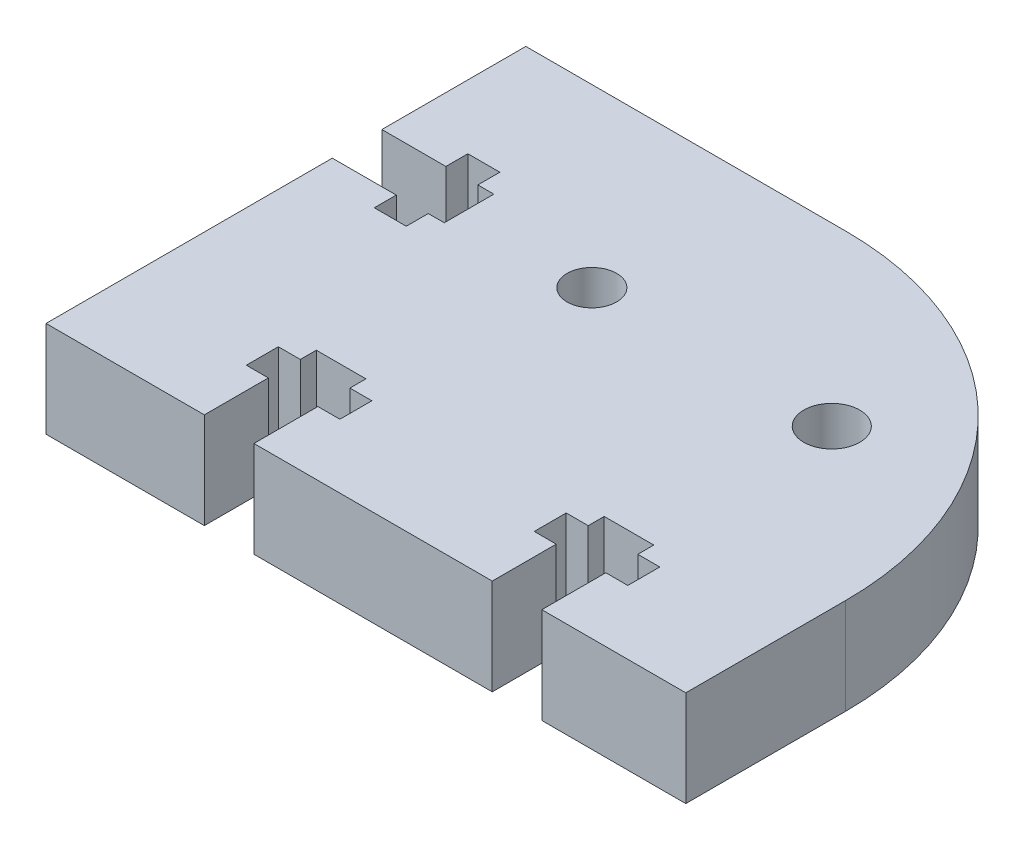
SolidWorks part; units mm, degrees
ref_plane "Płaszczyzna przednia" through (0, 0, 0) normal (0, 0, 1) x (1, 0, 0)
ref_plane "Płaszczyzna górna" through (0, 0, 0) normal (0, 1, 0) x (1, 0, 0)
ref_plane "Płaszczyzna prawa" through (0, 0, 0) normal (1, 0, 0) x (0, 0, -1)
sketch "Szkic3" plane through (0, 0, 0) normal (0, 1, 0) x (1, 0, 0)
  line L0 (-425.4385, -113.1796) -> (-425.4385, -103.1796)
  line L1 (-425.4385, -113.1796) -> (-465.4385, -113.1796)
  line L2 (-445.4385, -83.1796) -> (-465.4385, -83.1796)
  line L3 (-465.4385, -113.1796) -> (-465.4385, -83.1796)
  arc A0 (-425.4385, -103.1796) -> (-445.4385, -83.1796) centre (-445.4385, -103.1796) ccw
  dimension "D3" = 20
  dimension "D1" = 40
  dimension "D2" = 30
extrude "Dodanie-wyciągnięcie1" add sketch "Szkic3" along normal blind 6
sketch "Szkic4" plane through (0, 6, 0) normal (0, 1, 0) x (1, 0, 0)
  line L0 (-434.4385, -113.1796) -> (-437.5385, -113.1796)
  line L1 (-434.4385, -113.1796) -> (-434.4385, -109.1796)
  line L2 (-437.5385, -113.1796) -> (-437.5385, -109.1796)
  line L3 (-434.4385, -106.1796) -> (-437.5385, -106.1796)
  line L4 (-465.4385, -113.1796) -> (-425.4385, -113.1796) construction
  line L5 (-433.0635, -109.1796) -> (-433.0635, -107.1796)
  line L6 (-433.0635, -109.1796) -> (-434.4385, -109.1796)
  line L7 (-433.0635, -107.1796) -> (-434.4385, -107.1796)
  line L8 (-438.9135, -109.1796) -> (-438.9135, -107.1796)
  line L9 (-437.5385, -109.1796) -> (-438.9135, -109.1796)
  line L10 (-434.4385, -107.1796) -> (-434.4385, -106.1796)
  line L11 (-437.5385, -107.1796) -> (-438.9135, -107.1796)
  line L12 (-437.5385, -107.1796) -> (-437.5385, -106.1796)
  line L13 (-425.4385, -113.1796) -> (-425.4385, -103.1796) construction
  dimension "D1" = 5.85
  dimension "D2" = 3.1
  dimension "D3" = 1.375
  dimension "D4" = 1
  dimension "D5" = 2
  dimension "D6" = 7
  dimension "D7" = 9
extrude "Wytnij-wyciągnięcie1" cut sketch "Szkic4" against normal blind 6
pattern_linear "Szyk liniowy1" count 2 spacing 18 along (-1, 0, 0) of "Wytnij-wyciągnięcie1"
sketch "Szkic5" plane through (0, 6, 0) normal (0, 1, 0) x (1, 0, 0)
  line L0 (-465.4385, -95.2796) -> (-465.4385, -92.1796)
  line L1 (-465.4385, -95.2796) -> (-461.4385, -95.2796)
  line L2 (-465.4385, -92.1796) -> (-461.4385, -92.1796)
  line L3 (-458.4385, -95.2796) -> (-458.4385, -92.1796)
  line L4 (-465.4385, -83.1796) -> (-465.4385, -113.1796) construction
  line L5 (-459.4385, -96.6546) -> (-461.4385, -96.6546)
  line L6 (-459.4385, -96.6546) -> (-459.4385, -95.2796)
  line L7 (-461.4385, -96.6546) -> (-461.4385, -95.2796)
  line L8 (-459.4385, -90.8046) -> (-461.4385, -90.8046)
  line L9 (-459.4385, -95.2796) -> (-458.4385, -95.2796)
  line L10 (-459.4385, -92.1796) -> (-459.4385, -90.8046)
  line L11 (-461.4385, -92.1796) -> (-461.4385, -90.8046)
  line L12 (-459.4385, -92.1796) -> (-458.4385, -92.1796)
  line L13 (-445.4385, -83.1796) -> (-465.4385, -83.1796) construction
  dimension "D1" = 7
  dimension "D2" = 5.85
  dimension "D3" = 2
  dimension "D4" = 1
  dimension "D5" = 1.375
  dimension "D6" = 3.1
  dimension "D7" = 9
extrude "Wytnij-wyciągnięcie2" cut sketch "Szkic5" against normal blind 6
sketch "Szkic6" plane through (0, 6, 0) normal (0, 1, 0) x (1, 0, 0)
  line L0 (-452.4385, -113.1796) -> (-437.5385, -113.1796) construction
  circle A0 centre (-435.3104, -94.1796) radius 1.75
  circle A1 centre (-450.3104, -94.1796) radius 1.55
  dimension "D1" = 15
  dimension "D2" = 19
  dimension "D3" = 3.5
  dimension "D4" = 3.1
extrude "Wytnij-wyciągnięcie3" cut sketch "Szkic6" against normal blind 6
equation "\"tolerancja_wpusy\"=0.2"
equation "\"dlugosc_wpustu_duzy\"=20"
equation "\"srednica_otworu_M3\"=3.1"
equation "\"szerokosc_nogi_T\"=3.1"
equation "\"dlugosc_T_30\"=11"
equation "\"grubosc_na_nakretke_kwadrat\"=2"
equation "\"szerokosc_na_nakretke_kwadrat\"=5.85"
equation "\"wyokosc_nadstawki_T\"=0.5"
equation "\"dlugosc_T_20_6\"=14"
equation "\"D1@Szkic4\"=\"szerokosc_na_nakretke_kwadrat\""
equation "\"D2@Szkic4\"=\"szerokosc_nogi_T\""
equation "\"D3@Szkic4\"=(\"szerokosc_na_nakretke_kwadrat\"-\"szerokosc_nogi_T\")/2"
equation "\"D5@Szkic4\"=\"grubosc_na_nakretke_kwadrat\""
equation "\"D2@Szkic5\"=\"szerokosc_na_nakretke_kwadrat\""
equation "\"D3@Szkic5\"=\"grubosc_na_nakretke_kwadrat\""
equation "\"D5@Szkic5\"=(\"szerokosc_na_nakretke_kwadrat\"-\"szerokosc_nogi_T\")/2"
equation "\"D6@Szkic5\"=\"szerokosc_nogi_T\""
